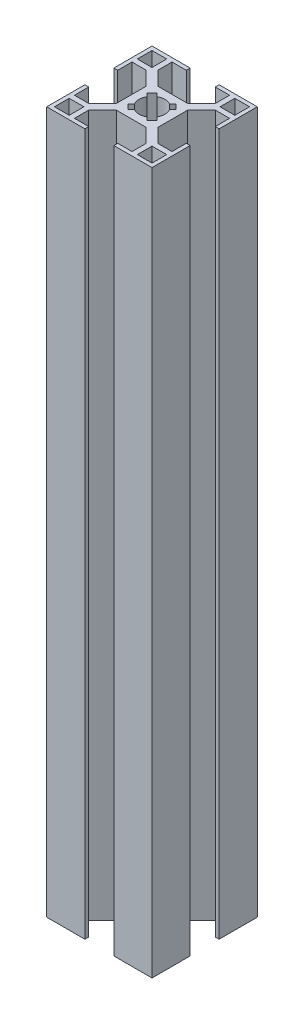
SolidWorks part; units mm, degrees
material "3.0255 (EN-AW 1350A)"
ref_plane "Alzado" through (0, 0, 0) normal (0, 0, 1) x (1, 0, 0)
ref_plane "Planta" through (0, 0, 0) normal (0, 1, 0) x (1, 0, 0)
ref_plane "Vista lateral" through (0, 0, 0) normal (1, 0, 0) x (0, 0, -1)
sketch "Croquis2" plane through (0, 0, 0) normal (0, 1, 0) x (1, 0, 0)
  line L0 (-12.6732, 23.1711) -> (-8.4732, 23.1711)
  line L1 (-37.3732, 24.2711) -> (-26.4982, 24.2711)
  line L2 (-37.3732, 24.2711) -> (-37.3732, 13.3961)
  line L3 (-37.3732, -5.7289) -> (-26.4982, -5.7289)
  line L4 (-7.3732, 24.2711) -> (-7.3732, 13.3961)
  line L5 (-30.5732, -4.6289) -> (-26.4982, -4.6289)
  line L6 (-30.5732, 23.1711) -> (-26.4982, 23.1711)
  line L7 (-36.2732, 5.1461) -> (-37.3732, 5.1461)
  line L8 (-8.4732, 23.1711) -> (-8.4732, 18.9711)
  line L9 (-36.2732, -4.6289) -> (-32.0732, -4.6289)
  line L10 (-36.2732, 23.1711) -> (-36.2732, 18.9711)
  line L11 (-36.2732, 23.1711) -> (-32.0732, 23.1711)
  line L12 (-32.0732, -0.4289) -> (-36.2732, -0.4289)
  line L15 (-8.4732, 18.9711) -> (-12.6732, 18.9711)
  line L16 (-12.6732, 23.1711) -> (-12.6732, 18.9711)
  line L17 (-32.0732, -0.4289) -> (-32.0732, -4.6289)
  line L19 (-36.2732, -0.4289) -> (-36.2732, -4.6289)
  line L21 (-32.0732, 23.1711) -> (-32.0732, 18.9711)
  line L22 (-32.0732, 18.9711) -> (-36.2732, 18.9711)
  line L24 (-8.4732, -0.4289) -> (-12.6732, -0.4289)
  line L25 (-8.4732, -0.4289) -> (-8.4732, -4.6289)
  line L26 (-8.4732, -4.6289) -> (-12.6732, -4.6289)
  line L27 (-12.6732, -0.4289) -> (-12.6732, -4.6289)
  line L28 (-26.5862, 3.3611) -> (-18.1603, 3.3611)
  line L29 (-16.4632, 13.4841) -> (-16.4632, 5.0582)
  line L30 (-26.5862, 15.1811) -> (-18.1603, 15.1811)
  line L31 (-28.2832, 13.4841) -> (-28.2832, 5.0582)
  line L32 (-28.2832, 15.1811) -> (-16.4632, 15.1811) construction
  line L33 (-28.2832, 3.3611) -> (-16.4632, 3.3611) construction
  line L34 (-7.3732, 5.1461) -> (-8.4732, 5.1461)
  line L35 (-7.3732, 13.3961) -> (-8.4732, 13.3961)
  line L36 (-26.4982, 24.2711) -> (-26.4982, 23.1711)
  line L37 (-18.2482, 24.2711) -> (-18.2482, 23.1711)
  line L38 (-36.2732, 13.3961) -> (-37.3732, 13.3961)
  line L39 (-19.1655, 11.0646) -> (-18.2482, 11.9819)
  line L40 (-36.2732, 5.1461) -> (-36.2732, 1.0711)
  line L41 (-36.2732, 23.1711) -> (-36.2732, -4.6289) construction
  line L42 (-37.3732, 5.1461) -> (-37.3732, -5.7289)
  line L43 (-37.3732, 24.2711) -> (-37.3732, -5.7289) construction
  line L44 (-18.2482, -4.6289) -> (-18.2482, -5.7289)
  line L46 (-8.4732, 5.1461) -> (-8.4732, 1.0711)
  line L47 (-8.4732, 23.1711) -> (-8.4732, -4.6289) construction
  line L48 (-7.3732, 5.1461) -> (-7.3732, -5.7289)
  line L49 (-7.3732, 24.2711) -> (-7.3732, -5.7289) construction
  line L51 (-25.084, 5.1461) -> (-24.1667, 6.0634)
  line L52 (-18.2482, -4.6289) -> (-14.1732, -4.6289)
  line L53 (-36.2732, -4.6289) -> (-8.4732, -4.6289) construction
  line L54 (-18.2482, -5.7289) -> (-7.3732, -5.7289)
  line L55 (-37.3732, -5.7289) -> (-7.3732, -5.7289) construction
  line L56 (-16.4632, 15.1811) -> (-16.4632, 3.3611) construction
  line L57 (-26.4982, 11.9819) -> (-25.5809, 11.0646)
  line L58 (-18.2482, 23.1711) -> (-14.1732, 23.1711)
  line L59 (-36.2732, 23.1711) -> (-8.4732, 23.1711) construction
  line L60 (-18.2482, 24.2711) -> (-7.3732, 24.2711)
  line L61 (-37.3732, 24.2711) -> (-7.3732, 24.2711) construction
  line L62 (-32.2703, 1.0711) -> (-36.2732, 1.0711)
  line L63 (-30.5732, 1.0711) -> (-37.7732, 1.0711) construction
  line L64 (-30.5732, 1.0711) -> (-30.5732, -6.1289) construction
  line L65 (-30.5732, -0.6259) -> (-30.5732, -4.6289)
  line L66 (-8.4732, 1.0711) -> (-12.4762, 1.0711)
  line L67 (-14.1732, -0.6259) -> (-14.1732, -4.6289)
  line L68 (-6.9732, 1.0711) -> (-6.9732, -6.1289) construction
  line L69 (-30.5732, -0.6259) -> (-26.5862, 3.3611)
  line L70 (-6.9732, 17.4711) -> (-14.1732, 17.4711) construction
  line L71 (-8.4732, 17.4711) -> (-12.4762, 17.4711)
  line L72 (-14.1732, 23.1711) -> (-14.1732, 19.1682)
  line L73 (-8.4732, 17.4711) -> (-8.4732, 13.3961)
  line L74 (-32.2703, 17.4711) -> (-36.2732, 17.4711)
  line L75 (-30.5732, 24.6711) -> (-30.5732, 17.4711) construction
  line L76 (-16.4632, 13.4841) -> (-12.4762, 17.4711)
  line L77 (-30.5732, 23.1711) -> (-30.5732, 19.1682)
  line L78 (-30.5732, -6.1289) -> (-37.7732, -6.1289) construction
  line L79 (-37.7732, 1.0711) -> (-37.7732, -6.1289) construction
  line L80 (-26.4982, -4.6289) -> (-26.4982, -5.7289)
  line L81 (-30.5732, 19.1682) -> (-26.5862, 15.1811)
  line L83 (-18.1603, 3.3611) -> (-14.1732, -0.6259)
  line L84 (-30.5732, 17.4711) -> (-37.7732, 17.4711) construction
  line L85 (-37.7732, 24.6711) -> (-37.7732, 17.4711) construction
  line L86 (-30.5732, 24.6711) -> (-37.7732, 24.6711) construction
  line L87 (-36.2732, 17.4711) -> (-36.2732, 13.3961)
  line L88 (-32.2703, 1.0711) -> (-28.2832, 5.0582)
  line L90 (-6.9732, -6.1289) -> (-14.1732, -6.1289) construction
  line L91 (-14.1732, 1.0711) -> (-14.1732, -6.1289) construction
  line L92 (-6.9732, 1.0711) -> (-14.1732, 1.0711) construction
  line L94 (-25.084, 13.3961) -> (-24.1667, 12.4788)
  line L95 (-19.1655, 7.4777) -> (-18.2482, 6.5603)
  line L96 (-20.5798, 6.0634) -> (-19.6624, 5.1461)
  line L97 (-14.1732, 24.6711) -> (-14.1732, 17.4711) construction
  line L98 (-6.9732, 24.6711) -> (-14.1732, 24.6711) construction
  line L99 (-6.9732, 24.6711) -> (-6.9732, 17.4711) construction
  line L100 (-16.4632, 5.0582) -> (-12.4762, 1.0711)
  line L101 (-26.4982, 6.5603) -> (-25.5809, 7.4777)
  line L104 (-28.2832, 15.1811) -> (-28.2832, 3.3611) construction
  line L105 (-18.1603, 15.1811) -> (-14.1732, 19.1682)
  line L106 (-32.2703, 17.4711) -> (-28.2832, 13.4841)
  line L111 (-20.5798, 12.4788) -> (-19.6624, 13.3961)
  line L114 (-26.4982, 6.5603) -> (-25.084, 5.1461)
  line L115 (-19.6624, 5.1461) -> (-18.2482, 6.5603)
  line L116 (-19.6624, 13.3961) -> (-18.2482, 11.9819)
  line L117 (-25.084, 13.3961) -> (-26.4982, 11.9819)
  line L119 (-32.0732, 23.1711) -> (-36.2732, 23.1711) construction
  line L120 (-8.4732, 23.1711) -> (-12.6732, 23.1711) construction
  line L121 (-32.0732, -4.6289) -> (-36.2732, -4.6289) construction
  line L122 (-8.4732, 23.1711) -> (-8.4732, 18.9711) construction
  line L123 (-36.2732, 23.1711) -> (-36.2732, 18.9711) construction
  arc A0 (-25.5809, 11.0646) -> (-25.5809, 7.4777) centre (-22.3732, 9.2711) ccw
  arc A1 (-20.5798, 12.4788) -> (-24.1667, 12.4788) centre (-22.3732, 9.2711) ccw
  arc A2 (-19.1655, 7.4777) -> (-19.1655, 11.0646) centre (-22.3732, 9.2711) ccw
  arc A3 (-24.1667, 6.0634) -> (-20.5798, 6.0634) centre (-22.3732, 9.2711) ccw
  dimension "D1" = 30
  dimension "D2" = 30
  dimension "D5" = 1.5
extrude "Saliente-Extruir1" add sketch "Croquis2" along normal blind 200
